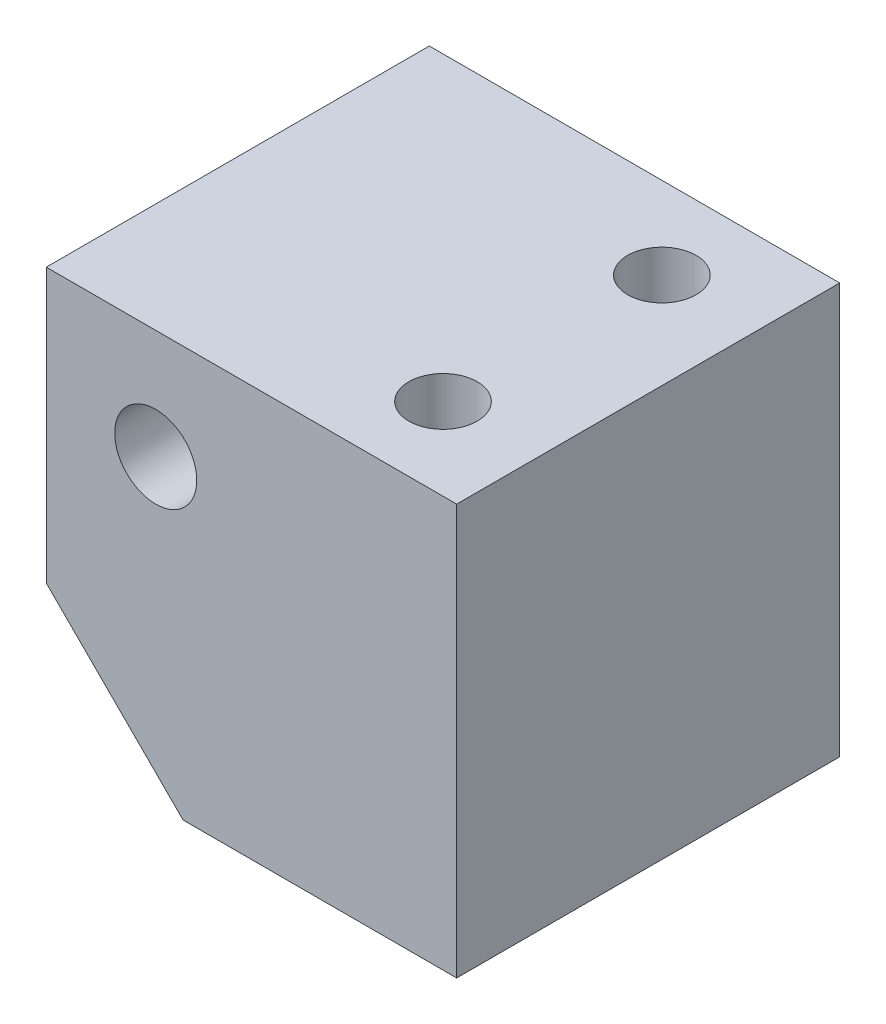
SolidWorks part; units mm, degrees
ref_plane "前视基准面" through (0, 0, 0) normal (0, 0, 1) x (1, 0, 0)
ref_plane "上视基准面" through (0, 0, 0) normal (0, 1, 0) x (1, 0, 0)
ref_plane "右视基准面" through (0, 0, 0) normal (1, 0, 0) x (0, 0, -1)
sketch "草图1" plane through (0, 0, 0) normal (0, 0, 1) x (1, 0, 0)
  line L0 (0, 0) -> (-5, 0)
  line L1 (0, 0) -> (10, 0)
  line L2 (0, 0) -> (0, -15)
  line L3 (0, -15) -> (10, -15)
  line L4 (10, 0) -> (10, -15)
  line L5 (-5, 0) -> (-5, -10)
  line L6 (-5, -10) -> (0, -15)
  circle A0 centre (-1, -4) radius 1.5
  dimension "D5" = 3
  dimension "D6" = 4
  dimension "D7" = 4
  dimension "D1" = 10
  dimension "D2" = 5
  dimension "D3" = 15
  dimension "D4" = 10
extrude "凸台-拉伸1" add sketch "草图1" along normal blind 14 contours L4 L1 L2 L3 | L5 L6 L2 L0 A0
sketch "草图2" plane through (0, 0, 0) normal (0, 1, 0) x (1, 0, 0)
  line L2 (10, -14) -> (10, 0) construction
  line L3 (10, -7) -> (-5, -7) construction
  line L4 (-5, -14) -> (-5, 0) construction
  circle A0 centre (6.5, -3) radius 1.25
  circle A1 centre (6.5, -11) radius 1.25
  dimension "D2" = 2.5
  dimension "D3" = 8
  dimension "D6" = 3.5
extrude "切除-拉伸1" cut sketch "草图2" against normal up to surface (15 mm away) up to face at (5, -15, 7)
cosmetic thread "装饰螺纹线1" parameters "D2"=3
cosmetic thread "装饰螺纹线2" parameters "D2"=3
